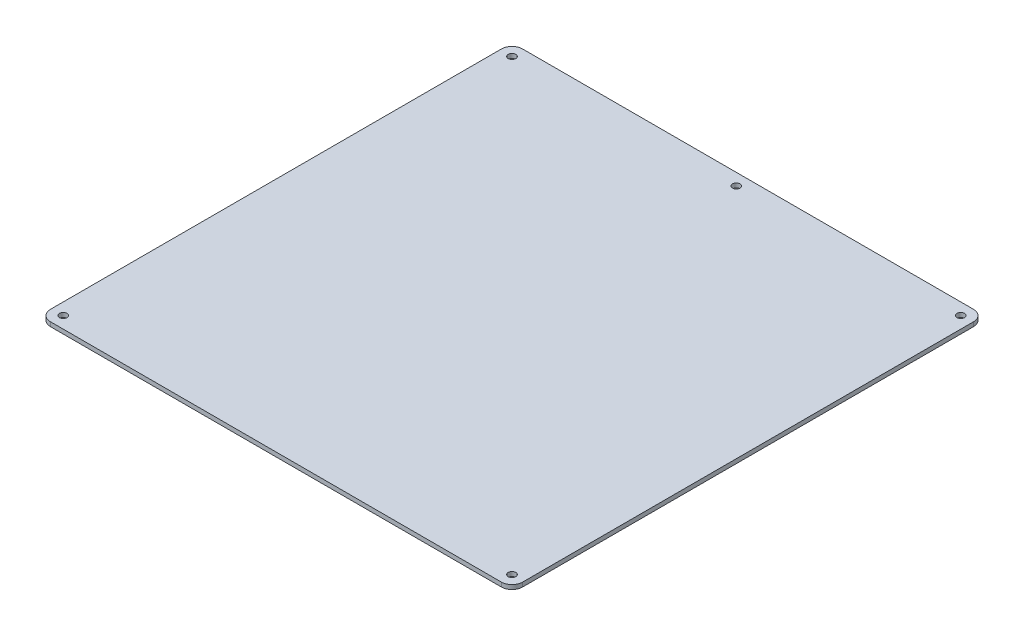
SolidWorks part; units mm, degrees
material "1060-H12"
ref_plane "Front" through (0, 0, 0) normal (0, 0, 1) x (1, 0, 0)
ref_plane "Top" through (0, 0, 0) normal (0, 1, 0) x (1, 0, 0)
ref_plane "Right" through (0, 0, 0) normal (1, 0, 0) x (0, 0, -1)
sketch "Эскиз1" plane through (0, 0, 0) normal (0, 1, 0) x (1, 0, 0)
  line L1 (-105, 110) -> (105, 110)
  line L2 (-110, 105) -> (-110, -105)
  line L3 (-105, -110) -> (105, -110)
  line L4 (110, 105) -> (110, -105)
  line L5 (-110, 110) -> (110, -110) construction
  line L6 (-110, -110) -> (110, 110) construction
  circle A0 centre (104.5, 104.5) radius 1.75
  circle A1 centre (104.5, -104.5) radius 1.75
  circle A2 centre (0, 104.5) radius 1.75
  circle A3 centre (-104.5, 104.5) radius 1.75
  circle A4 centre (-104.5, -104.5) radius 1.75
  arc A5 (-110, -105) -> (-105, -110) centre (-105, -105) ccw
  arc A6 (105, -110) -> (110, -105) centre (105, -105) ccw
  arc A7 (105, 110) -> (110, 105) centre (105, 105) cw
  arc A8 (-110, 105) -> (-105, 110) centre (-105, 105) cw
  point P0 (0, 0)
  dimension "D3" = 3.5
  dimension "D4" = 3.5
  dimension "D6" = 209
  dimension "D7" = 3.5
  dimension "D8" = 3.5
  dimension "D9" = 5.5
  dimension "D10" = 5.5
  dimension "D12" = 3.5
  dimension "D13" = 5.5
  dimension "D14" = 5.5
  dimension "D15" = 5
  dimension "D1" = 220
  dimension "D2" = 220
  dimension "D5" = 5.5
  dimension "D11" = 5.5
extrude "Бобышка-Вытянуть1" add sketch "Эскиз1" along normal blind 2
